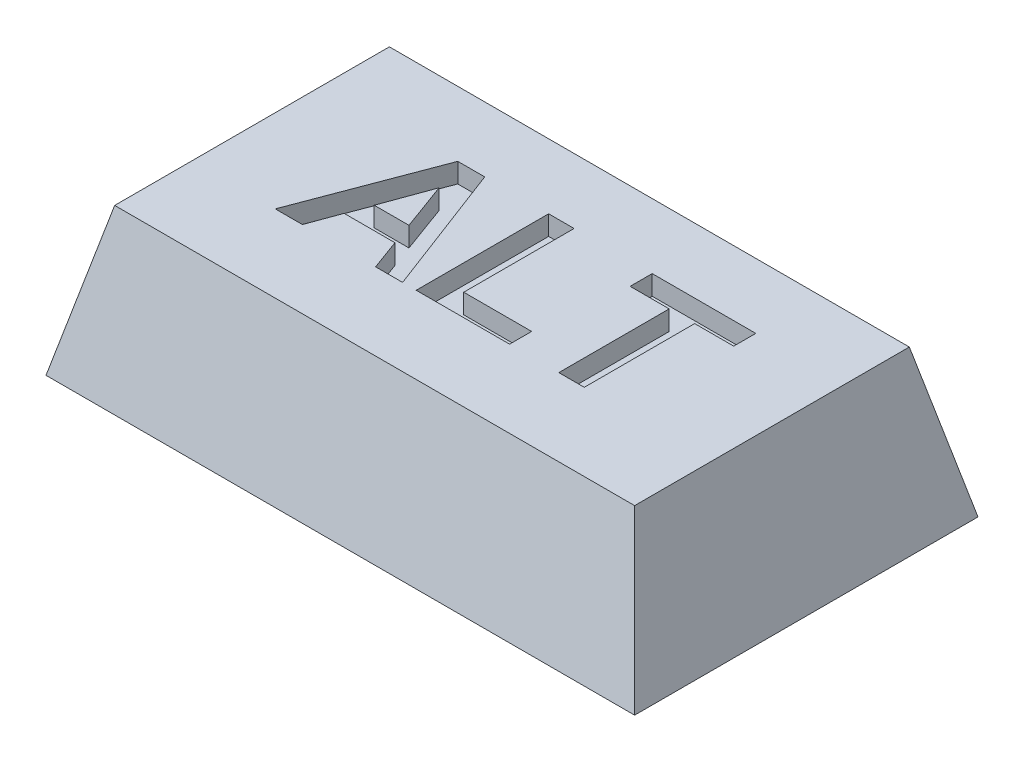
SolidWorks part; units mm, degrees
ref_plane "Front Plane" through (0, 0, 0) normal (0, 0, 1) x (1, 0, 0)
ref_plane "Top Plane" through (0, 0, 0) normal (0, 1, 0) x (1, 0, 0)
ref_plane "Right Plane" through (0, 0, 0) normal (1, 0, 0) x (0, 0, -1)
sketch "Sketch1" plane through (0, 0, 0) normal (0, 1, 0) x (1, 0, 0)
  line L1 (0, 0) -> (12, 0)
  line L2 (0, 0) -> (0, 7)
  line L3 (0, 7) -> (12, 7)
  line L4 (12, 0) -> (12, 7)
  dimension "D1" = 7
  dimension "D2" = 12
extrude "Boss-Extrude1" add sketch "Sketch1" along normal blind 3
sketch "Sketch2" plane through (0, 0, 0) normal (0, 0, 1) x (1, 0, 0)
  line L0 (0, 0) -> (0.7, 3)
  line L1 (0, 3) -> (12, 3) construction
  line L2 (0.7, 3) -> (0, 3)
  line L3 (0, 3) -> (0, 0)
  line L4 (12, 0) -> (11.3, 3)
  line L5 (11.3, 3) -> (12, 3)
  line L6 (12, 3) -> (12, 0)
  dimension "D1" = 0.7
  dimension "D2" = 0.7
extrude "Cut-Extrude1" cut sketch "Sketch2" against normal blind 7
sketch "Sketch3" plane through (0, 0, 0) normal (1, 0, 0) x (0, 0, -1)
  line L0 (0, 0) -> (0.7, 3)
  line L1 (7, 3) -> (0, 3) construction
  line L2 (0.7, 3) -> (0, 3)
  line L3 (0, 3) -> (0, 0)
  line L4 (7, 3) -> (6.3, 3)
  line L5 (6.3, 3) -> (7, 0)
  line L6 (7, 3) -> (7, 0)
  dimension "D1" = 0.7
  dimension "D2" = 0.7
extrude "Cut-Extrude2" cut sketch "Sketch3" along normal through all both and the other way through all
sketch "Sketch4" plane through (0, 0, 0) normal (0, -1, 0) x (1, 0, 0)
  line L0 (6, 0) -> (6, -7) construction
  line L1 (0, 0) -> (12, 0) construction
  line L2 (12, -7) -> (0, -7) construction
  line L3 (0, -3.5) -> (12, -3.5) construction
  line L4 (0, -7) -> (0, 0) construction
  line L5 (12, 0) -> (12, -7) construction
  circle A0 centre (6, -3.5) radius 1.8
  dimension "D1" = 3.6
extrude "Cut-Extrude3" cut sketch "Sketch4" against normal blind 0.8
sketch "Sketch5" plane through (0, 3, 0) normal (0, 1, 0) x (1, 0, 0)
  text T0 "ALT" font "Arial" height 2.7
extrude "Cut-Extrude4" cut sketch "Sketch5" against normal blind 0.4
